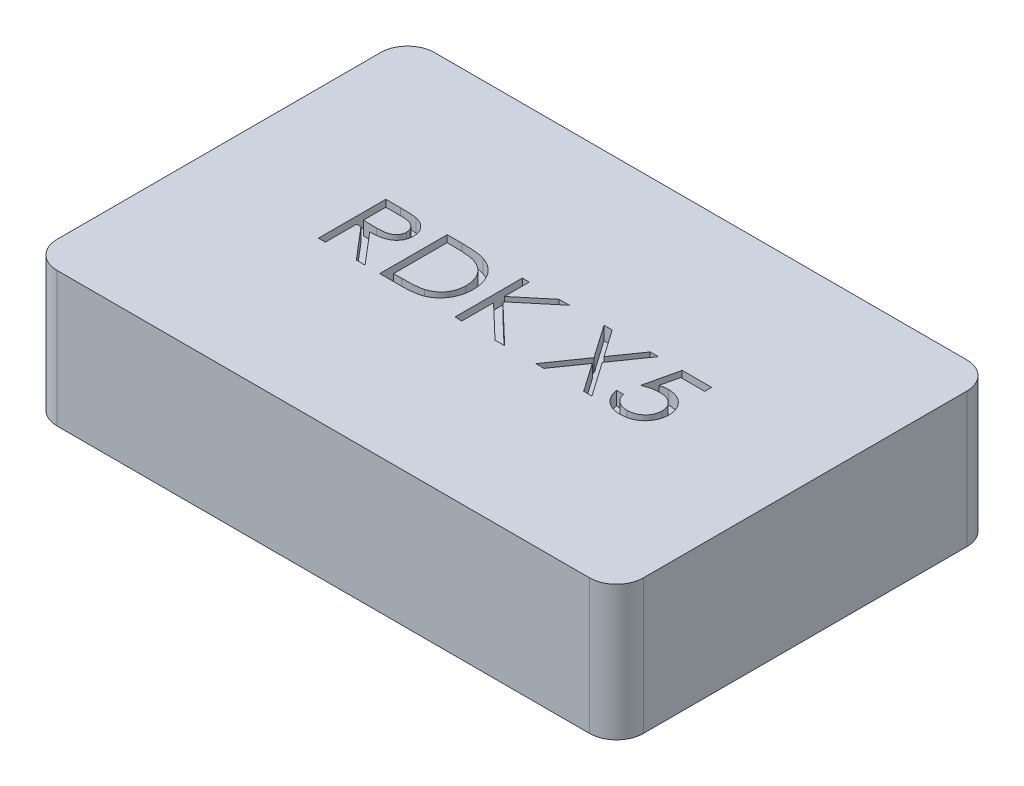
SolidWorks part; units mm, degrees
material "1060-H12 棒材(SS)"
ref_plane "Front Plane" through (0, 0, 0) normal (0, 0, 1) x (1, 0, 0)
ref_plane "Top Plane" through (0, 0, 0) normal (0, 1, 0) x (1, 0, 0)
ref_plane "Right Plane" through (0, 0, 0) normal (1, 0, 0) x (0, 0, -1)
other "Configuration Table"
sketch "草图1" plane through (0, 0, 0) normal (0, 1, 0) x (1, 0, 0)
  line L1 (-24.3314, 21.8924) -> (62.6686, 21.8924)
  line L2 (-24.3314, 21.8924) -> (-24.3314, -34.1076)
  line L3 (-24.3314, -34.1076) -> (62.6686, -34.1076)
  line L4 (62.6686, 21.8924) -> (62.6686, -34.1076)
  dimension "D1" = 87
  dimension "D2" = 56
extrude "凸台-拉伸1" add sketch "草图1" along normal blind 20
fillet "圆角1" radius 4 4 edges at (-24.3314, 10, -21.8924) (62.6686, 10, -21.8924) (62.6686, 10, 34.1076) (-24.3314, 10, 34.1076)
sketch "草图2" plane through (0, 20, 0) normal (0, 1, 0) x (1, 0, 0)
  text T0 "RDK X5" font "Century Gothic" height 10
extrude "切除-拉伸1" cut sketch "草图2" against normal blind 2
